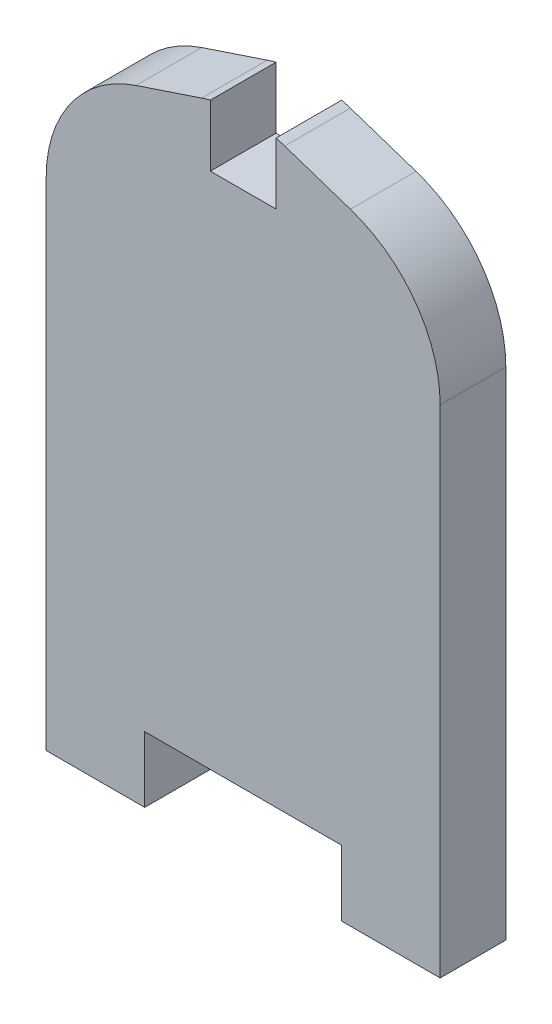
SolidWorks part; units mm, degrees
ref_plane "Front Plane" through (0, 0, 0) normal (0, 0, 1) x (1, 0, 0)
ref_plane "Top Plane" through (0, 0, 0) normal (0, 1, 0) x (1, 0, 0)
ref_plane "Right Plane" through (0, 0, 0) normal (1, 0, 0) x (0, 0, -1)
sketch "Sketch1" plane through (0, 0, 0) normal (0, 0, 1) x (1, 0, 0)
  line L0 (0, 19.1809) -> (0, -31.75) construction
  line L1 (-9.525, -37.9691) -> (9.525, -37.9691)
  line L2 (-19.05, -37.9691) -> (-19.05, 12.8309)
  line L4 (19.05, -37.9691) -> (19.05, 12.8309)
  line L5 (-19.05, 12.8309) -> (0, 19.1809)
  line L6 (0, 19.1809) -> (19.05, 12.8309)
  line L8 (-19.05, -37.9691) -> (-19.05, -44.3191)
  line L9 (-19.05, -44.3191) -> (-9.525, -44.3191)
  line L10 (-9.525, -37.9691) -> (-9.525, -44.3191)
  line L11 (9.525, -37.9691) -> (9.525, -44.3191)
  line L12 (19.05, -44.3191) -> (9.525, -44.3191)
  line L13 (19.05, -37.9691) -> (19.05, -44.3191)
  line L14 (-19.05, 12.8309) -> (19.05, 12.8309) construction
  point P0 (0, 0)
  dimension "D3" = 6.35
  dimension "D4" = 9.525
  dimension "D2" = 6.35
  dimension "D1" = 50.8
extrude "Boss-Extrude1" add sketch "Sketch1" along normal blind 6.35
fillet "Fillet1" radius 12.7 3 edges at (19.05, 12.8309, 3.175) (-19.05, 12.8309, 3.175) (0, 19.1809, 3.175)
sketch "Sketch5" plane through (0, 0, 6.35) normal (0, 0, 1) x (1, 0, 0)
  line L0 (0, 25.5944) -> (0, -32.9238) construction
  line L2 (-3.175, 12.144) -> (3.175, 12.144)
  line L3 (-3.175, 12.144) -> (-3.175, 24.844)
  line L4 (-3.175, 24.844) -> (3.175, 24.844)
  line L5 (3.175, 12.144) -> (3.175, 24.844)
  line L6 (-3.175, 12.144) -> (3.175, 24.844) construction
  line L7 (-3.175, 24.844) -> (3.175, 12.144) construction
  arc A0 (4.0161, 17.8422) -> (-4.0161, 17.8422) centre (0, 5.794) ccw construction
  point P3 (0, 18.494)
  dimension "D1" = 6.35
  dimension "D2" = 6.35
extrude "Cut-Extrude1" cut sketch "Sketch5" against normal through all both and the other way through all
equation "\"Wheel Thickness\"= 1in"
equation "\"Wheel Diameter\"= 3in"
equation "\"Motor Rear Diameter\" = 36.2mm"
equation "\"Motor Front Diameter\" = 12mm"
equation "\"Material Thickness\" = .25in"
equation "\"Wheel Cutout Diameter\"= 2cm"
equation "\"Motor Mount Tab Thickness\" = 100mm"
equation "\"Motor Mount Tab Height\" = 40mm"
equation "\"Motor Shaft Diameter\" = 3mm"
equation "\"Wheel Radius Clearance\" = 5mm"
equation "\"Wheel Cutout Width\" = 1.5in"
equation "\"Base Diameter\" = 10in"
equation "\"Wheel Mount Distance\" = 5mm"
equation "\"Motor Mount Distance\" = 50mm"
equation "\"Motor Cutout Length\" = 6in"
equation "\"Motor Cutout Height\" = 2in "
equation "\"Rod Diameter\" = 3/8in"
equation "\"Rod Length\" = 1.5in"
equation "\"Barrel Front Length\" = 1.8in"
equation "\"Barrerl Rear Length\" = 5in "
equation "\"Barrel Fillet Radius\" = 1in "
equation "\"Barrel Angle\" = 20deg"
equation "\"Barrel Diameter\" = 50mm"
equation "\"Barrel Shell Width\" = 2mm"
equation "\"Second Level Diameter\" = 10in"
equation "\"Ball Diameter\" = 40mm"
equation "\"Third Level Length\" = 9in"
equation "\"Third Level Height\" = 9in"
equation "\"Barrel Tab Clearance\" = 5mm"
equation "\"Barrel Tab Distance Away\" = 2mm"
equation "\"Hole Distance Apart\" = 2.8in"
equation "\"Barrel Tab Distance\"= 1.5in "
equation "\"Third Level Rod Distance\" = .5in"
equation " \"Second Rod Diameter\" = 3/8in"
equation "\"Second Rod Length\" = 3.88in"
equation "\"Bumper Wheel Clearance\" = 1.2in"
equation "\"Servo Tab Height\" = 4in"
equation "\"Servo Tab Width\" = 2in"
equation "\"Servo Tab Hole Horizontal Distance\" = 1in"
equation "\"Servo Tab Hole Vertical Distance\" = 1.5in "
equation "\"Servo Hole Vertical Distance\" = 3in"
equation "\"Servo Hole Diameter\" = 1/4in"
equation "\"Servo Hole Shaft Length\" = 1.45in"
equation "\"Third Rod Length\" = 3.83in"
equation "\"Third Rod Diameter\" = 3/8in"
equation "\"Third Rod Radius Distance\" = 1.5in"
equation "\"Third Rod Angle Distance\" = 20deg"
equation "\"Fourth Level Diameter\" = 3.5in"
equation "\"Skid Length\" = 2in"
equation "\"Skid Width\" = 1.5in"
equation "\"Skid Clearance\" = 3mm"
equation "\"D1@Boss-Extrude1\"=\"Material Thickness\""
equation "\"Skid Cut Distance\" = .25in"
equation "\"Skid Fillet Radius\" = .5in"
equation "\"D3@Sketch1\"=\"Material Thickness\""
equation "\"D4@Sketch1\"=\"Skid Width\"/4"
equation "\"D1@Fillet1\"=\"Skid Fillet Radius\""
equation "\"D2@Sketch5\"=\"Material Thickness\""
equation "\"D1@Sketch1\"=\"Skid Length\""
equation "\"D2@Sketch1\"=\"Skid Length\"/8"
equation "\"D1@Sketch5\"=\"Skid Cut Distance\""
equation "\"D2@Sketch2\"=\"Material Thickness\""
